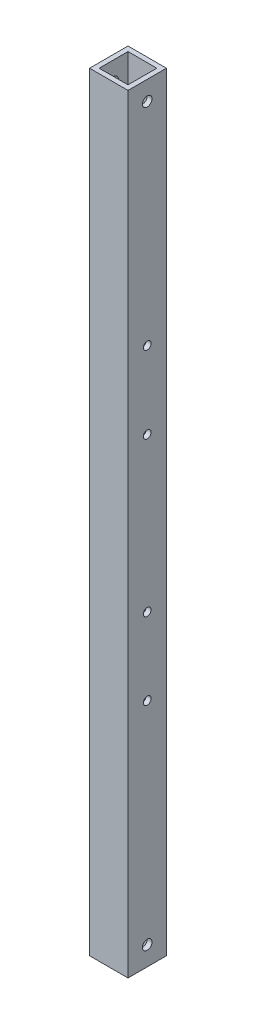
SolidWorks part; units mm, degrees
ref_plane "Front Plane" through (0, 0, 0) normal (0, 0, 1) x (1, 0, 0)
ref_plane "Top Plane" through (0, 0, 0) normal (0, 1, 0) x (1, 0, 0)
ref_plane "Right Plane" through (0, 0, 0) normal (1, 0, 0) x (0, 0, -1)
sketch "Sketch1" plane through (0, 0, 0) normal (0, 1, 0) x (1, 0, 0)
  line L0 (3.175, 3.175) -> (3.175, 22.225)
  line L1 (0, 0) -> (25.4, 0)
  line L2 (0, 0) -> (0, 25.4)
  line L3 (0, 25.4) -> (25.4, 25.4)
  line L4 (25.4, 0) -> (25.4, 25.4)
  line L5 (3.175, 22.225) -> (22.225, 22.225)
  line L6 (22.225, 3.175) -> (22.225, 22.225)
  line L7 (3.175, 3.175) -> (22.225, 3.175)
  dimension "D1" = 25.4
  dimension "D2" = 25.4
  dimension "D3" = 3.175
extrude "Boss-Extrude1" add sketch "Sketch1" along normal blind 508
sketch "Sketch2" plane through (25.4, 0, 0) normal (1, 0, 0) x (0, 0, -1)
  line L0 (25.4, 508) -> (25.4, 0) construction
  line L1 (13.97, 0) -> (-13.97, 0) construction
  circle A0 centre (12.7, 12.7) radius 3.175
  dimension "D1" = 6.35
  dimension "D2" = 12.7
  dimension "D3" = 12.7
extrude "Cut-Extrude1" cut sketch "Sketch2" against normal through all
ref_plane "Plane1" through (0, 254, 0) normal (0, 1, 0) x (1, 0, 0)
mirror "Mirror1" about plane through (0, 254, 0) normal (0, 1, 0) of "Cut-Extrude1"
sketch "Sketch3" plane through (25.4, 0, 0) normal (1, 0, 0) x (0, 0, -1)
  circle A0 centre (12.7, 304.8) radius 2.5797
  circle A1 centre (12.7, 355.6) radius 2.5797
  circle A2 centre (12.7, 203.2) radius 2.5797
  circle A3 centre (12.7, 152.4) radius 2.5797
extrude "Cut-Extrude2" cut sketch "Sketch3" against normal up to next
